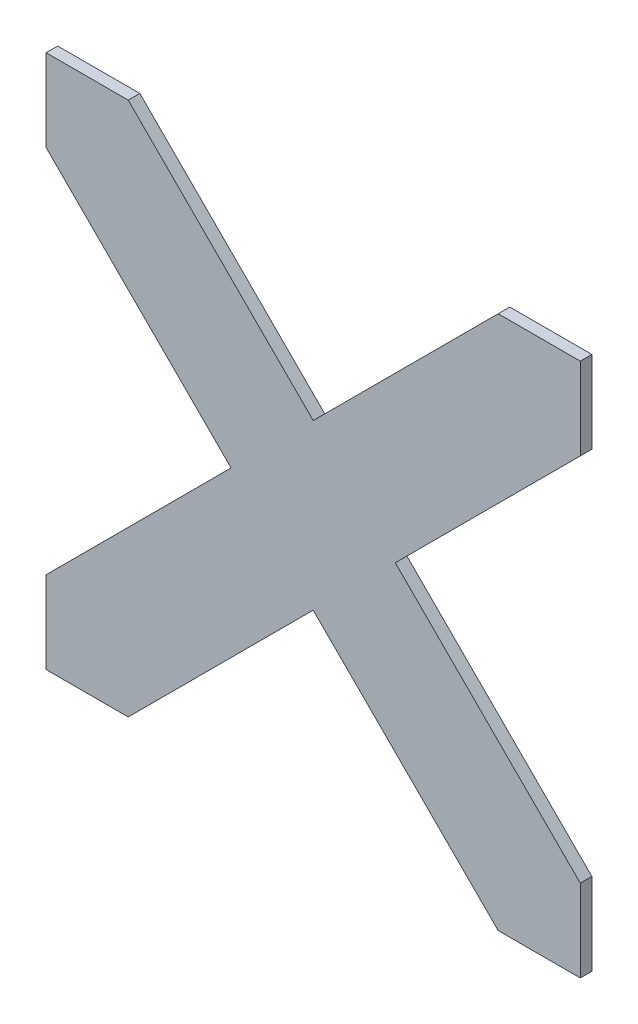
SolidWorks part; units mm, degrees
ref_plane "Front Plane" through (0, 0, 0) normal (0, 0, 1) x (1, 0, 0)
ref_plane "Top Plane" through (0, 0, 0) normal (0, 1, 0) x (1, 0, 0)
ref_plane "Right Plane" through (0, 0, 0) normal (1, 0, 0) x (0, 0, -1)
sketch "Sketch7" plane through (0, 0, 0) normal (0, 0, 1) x (1, 0, 0)
  line L0 (-78.549, 130.1171) -> (38.2378, 13.3303)
  line L1 (-99.7622, 130.1171) -> (38.2378, 130.1171) construction
  line L4 (38.2378, -7.8829) -> (-99.7622, -7.8829) construction
  line L6 (-99.7622, -7.8829) -> (-99.7622, 130.1171) construction
  line L9 (17.0246, -7.8829) -> (38.2378, -7.8829)
  line L11 (17.0246, -7.8829) -> (-99.7622, 108.9039)
  line L12 (-78.549, 130.1171) -> (-99.7622, 130.1171)
  line L15 (38.2378, 130.1171) -> (38.2378, -7.8829) construction
  line L16 (-99.7622, 130.1171) -> (-99.7622, 108.9039)
  line L17 (38.2378, -7.8829) -> (38.2378, 13.3303)
  line L18 (-20.1556, 71.7237) -> (-41.3688, 50.5105) construction
  point P15 (-30.7622, 130.1171)
  point P20 (-30.7622, 61.1171)
  point P21 (38.2378, 61.1171)
  point P22 (0, 0)
  point P23 (0, 0)
  point P24 (17.569, -7.8829)
  point P25 (0, 0)
  dimension "D1" = 30
extrude "Boss-Extrude1" add sketch "Sketch7" along normal blind 3
sketch "Sketch8" plane through (0, 0, 0) normal (0, 0, 1) x (1, 0, 0)
  line L0 (-78.549, -7.8829) -> (38.2378, 108.9039)
  line L1 (-99.7622, -7.8829) -> (38.2378, -7.8829) construction
  line L4 (38.2378, 130.1171) -> (-99.7622, 130.1171) construction
  line L6 (-99.7622, 130.1171) -> (-99.7622, -7.8829) construction
  line L9 (17.0246, 130.1171) -> (38.2378, 130.1171)
  line L11 (17.0246, 130.1171) -> (-99.7622, 13.3303)
  line L12 (-78.549, -7.8829) -> (-99.7622, -7.8829)
  line L15 (38.2378, -7.8829) -> (38.2378, 130.1171) construction
  line L16 (-99.7622, -7.8829) -> (-99.7622, 13.3303)
  line L17 (38.2378, 130.1171) -> (38.2378, 108.9039)
  line L18 (-20.1556, 50.5105) -> (-41.3688, 71.7237) construction
  point P4 (-85.4003, 66.8291)
  point P5 (0, 0)
  point P6 (0, 0)
  point P7 (0, 0)
  point P8 (-99.7622, -29.0961)
  point P10 (0, 0)
  point P11 (38.2378, 151.3303)
  point P13 (38.2378, 106.2335)
  point P15 (-30.7622, -7.8829)
  point P20 (-30.7622, 61.1171)
  point P21 (38.2378, 61.1171)
  point P22 (0, 0)
  point P23 (0, 0)
  point P24 (17.569, -7.8829)
  point P25 (0, 0)
  dimension "D1" = 30
extrude "Boss-Extrude2" add sketch "Sketch8" along normal blind 3
